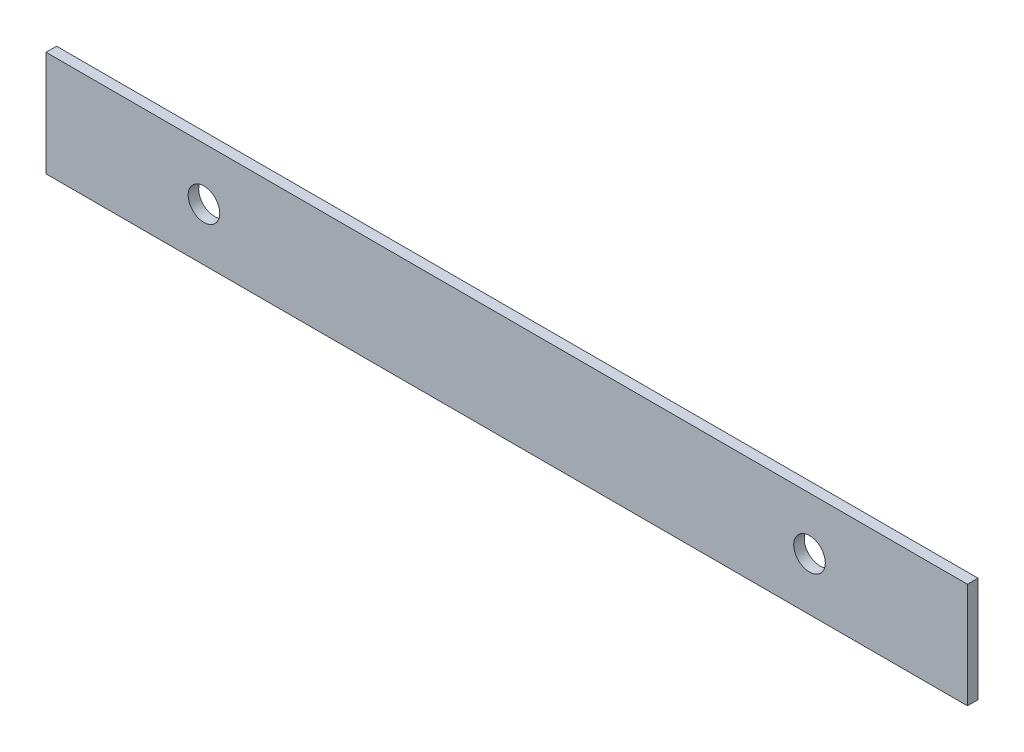
SolidWorks part; units mm, degrees
ref_plane "Спереди" through (0, 0, 0) normal (0, 0, 1) x (1, 0, 0)
ref_plane "Сверху" through (0, 0, 0) normal (0, 1, 0) x (1, 0, 0)
ref_plane "Справа" through (0, 0, 0) normal (1, 0, 0) x (0, 0, -1)
sketch "Эскиз1" plane through (0, 0, 0) normal (0, 0, 1) x (1, 0, 0)
  line L1 (0, 0) -> (350, 0)
  line L2 (0, 0) -> (0, 40)
  line L3 (0, 40) -> (350, 40)
  line L4 (350, 0) -> (350, 40)
  dimension "D1" = 40
  dimension "D2" = 350
extrude "Бобышка-Вытянуть1" add sketch "Эскиз1" along normal blind 4
sketch "Эскиз2" plane through (0, 0, 4) normal (0, 0, 1) x (1, 0, 0)
  line L0 (0, 40) -> (0, 0) construction
  line L1 (350, 40) -> (0, 40) construction
  circle A0 centre (60, 20) radius 6
  dimension "D1" = 60
  dimension "D2" = 20
extrude "Вырез-Вытянуть1" cut sketch "Эскиз2" against normal through all
sketch "Эскиз3" plane through (0, 0, 4) normal (0, 0, 1) x (1, 0, 0)
  line L0 (350, 40) -> (0, 40) construction
  line L1 (350, 0) -> (350, 40) construction
  circle A0 centre (290, 20) radius 6
  dimension "D1" = 20
  dimension "D2" = 60
extrude "Вырез-Вытянуть2" cut sketch "Эскиз3" against normal through all
